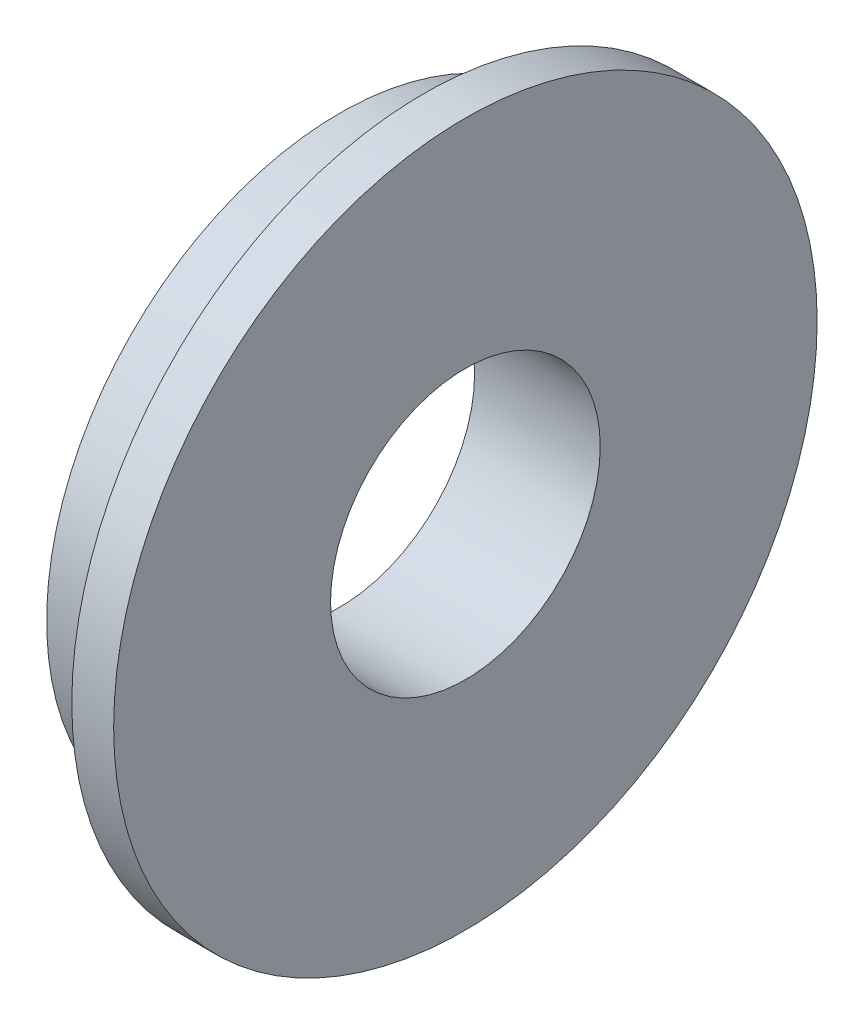
SolidWorks part; units mm, degrees
material "PLA2"
ref_plane "Front Plane" through (0, 0, 0) normal (0, 0, 1) x (1, 0, 0)
ref_plane "Top Plane" through (0, 0, 0) normal (0, 1, 0) x (1, 0, 0)
ref_plane "Right Plane" through (0, 0, 0) normal (1, 0, 0) x (0, 0, -1)
sketch "Sketch1" plane through (0, 0, 0) normal (1, 0, 0) x (0, 0, -1)
  circle A0 centre (0, 0) radius 2.0447
  circle A1 centre (0, 0) radius 4.445
  dimension "D1" = 4.0894
  dimension "D2" = 8.89
extrude "Boss-Extrude1" add sketch "Sketch1" along normal blind 1.27
sketch "Sketch2" plane through (1.27, 0, 0) normal (-1, 0, 0) x (0, 0, 1)
  circle A0 centre (0, 0) radius 5.334
  circle A1 centre (0, 0) radius 2.0447 construction
  circle A2 centre (0, 0) radius 2.0447
  dimension "D1" = 10.668
extrude "Boss-Extrude2" add sketch "Sketch2" against normal blind 0.635
